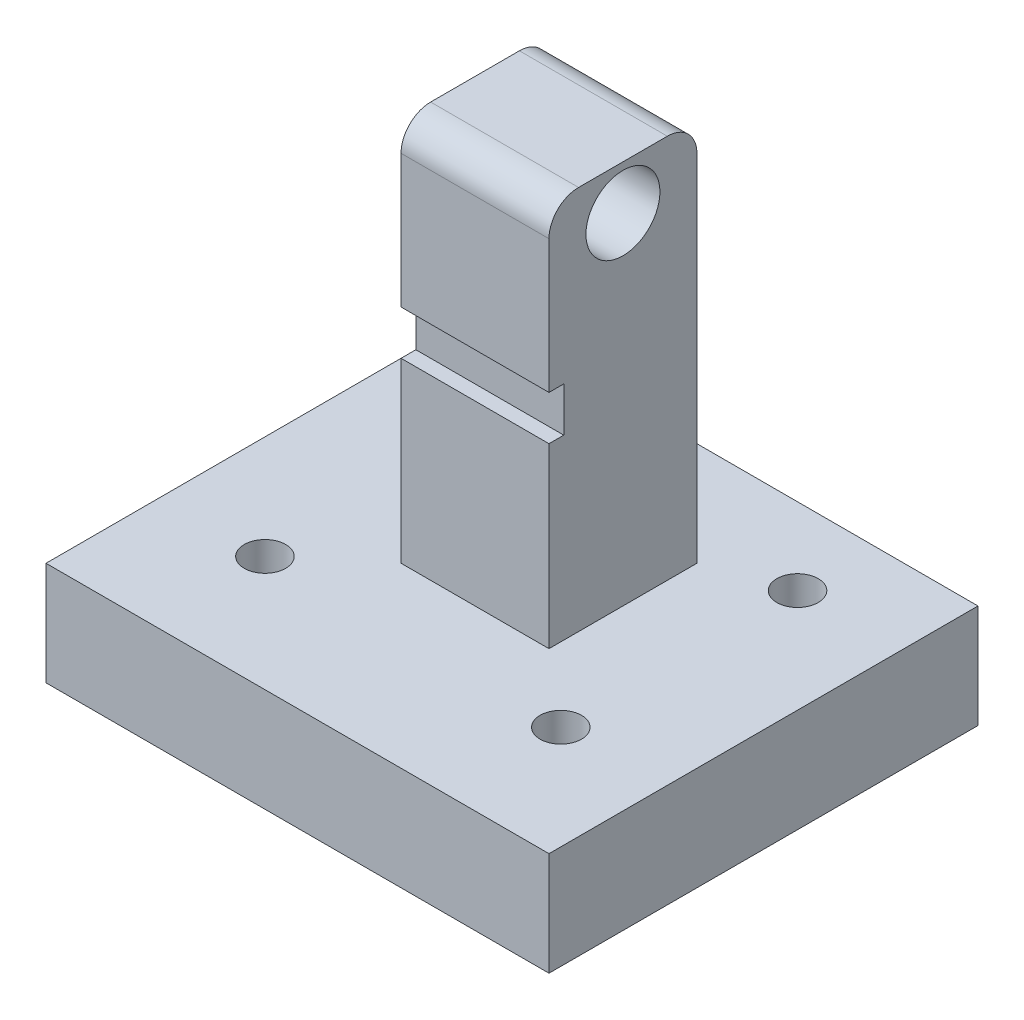
SolidWorks part; units mm, degrees
ref_plane "Front Plane" through (0, 0, 0) normal (0, 0, 1) x (1, 0, 0)
ref_plane "Top Plane" through (0, 0, 0) normal (0, 1, 0) x (1, 0, 0)
ref_plane "Right Plane" through (0, 0, 0) normal (1, 0, 0) x (0, 0, -1)
sketch "Sketch2" plane through (0, 0, 0) normal (0, 0, 1) x (1, 0, 0)
  line L1 (-73.75, 88.375) -> (73.75, 88.375)
  line L2 (-73.75, 88.375) -> (-73.75, -88.375)
  line L3 (-73.75, -88.375) -> (73.75, -88.375)
  line L4 (73.75, 88.375) -> (73.75, -88.375)
  line L5 (-73.75, 88.375) -> (73.75, -88.375) construction
  line L6 (-73.75, -88.375) -> (73.75, 88.375) construction
  point P0 (0, 0)
  dimension "D1" = 147.5
  dimension "D2" = 176.75
extrude "Boss-Extrude1" add sketch "Sketch2" along normal blind 10
sketch "Sketch3" plane through (-73.75, 0, 0) normal (-1, 0, 0) x (0, 0, 1)
  line L0 (0, 88.375) -> (0, -88.375) construction
  line L1 (-7, 88.375) -> (22, 88.375)
  line L2 (-7, 88.375) -> (-7, 73.375)
  line L3 (-7, 73.375) -> (22, 73.375)
  line L4 (22, 88.375) -> (22, 73.375)
  line L5 (10, 88.375) -> (10, -88.375) construction
  line L6 (0, 0) -> (56.8374, 0) construction
  line L7 (22, -88.375) -> (22, -73.375)
  line L8 (-7, -88.375) -> (-7, -73.375)
  line L9 (-7, -88.375) -> (22, -88.375)
  line L10 (-7, -73.375) -> (22, -73.375)
  line L11 (10, 88.375) -> (0, 88.375) construction
  dimension "D1" = 7
  dimension "D2" = 12
  dimension "D3" = 15
  dimension "D4" = 0
extrude "Boss-Extrude2" add sketch "Sketch3" against normal blind 34
ref_plane "Plane1" through (0, 0, 0) normal (1, 0, 0) x (0, 0, -1)
mirror "Mirror1" about plane through (0, 0, 0) normal (1, 0, 0) of "Boss-Extrude2"
sketch "Sketch5" plane through (-73.75, 0, 0) normal (-1, 0, 0) x (0, 0, 1)
  line L0 (10, 73.375) -> (10, -73.375) construction
  line L1 (-35, 0) -> (-35, 43.6802) construction
  line L2 (0, 0) -> (0, 73.375) construction
  line L3 (0, 0) -> (10, 0)
  line L4 (-35, 0) -> (0, 0) construction
  line L5 (-7, 88.375) -> (22, 88.375)
  line L6 (-7, 88.375) -> (-7, 73.375)
  line L7 (-7, 73.375) -> (22, 73.375)
  line L8 (22, 88.375) -> (22, 73.375)
  line L9 (0, 73.375) -> (10, 73.375)
  line L10 (0, 73.375) -> (0, 0)
  line L11 (0, 0) -> (10, 0)
  line L12 (10, 73.375) -> (10, 0)
  line L13 (5, 0) -> (5, -4.9122)
  line L18 (58.2224, 51.916) -> (50.0308, 46.1802)
  line L19 (-7, 73.375) -> (22, 73.375)
  line L20 (-7, 73.375) -> (-7, 63.375)
  line L21 (-7, 63.375) -> (22, 63.375)
  line L22 (22, 73.375) -> (22, 63.375)
  line L23 (50.0308, 46.1802) -> (66.6646, 22.4248)
  line L24 (58.2224, 51.916) -> (74.8561, 28.1606)
  line L25 (74.8561, 28.1606) -> (66.6646, 22.4248)
  line L26 (67.9732, 37.9904) -> (7.8679, -4.0958)
  line L27 (62.2374, 46.1819) -> (2.1321, 4.0958)
  line L28 (2.1321, 4.0958) -> (7.8679, -4.0958)
  line L29 (2.1321, -4.0958) -> (7.8679, 4.0958)
  line L30 (62.2374, -46.1819) -> (2.1321, -4.0958)
  line L31 (67.9732, -37.9904) -> (7.8679, 4.0958)
  line L32 (5, 0) -> (5, 4.9122)
  line L33 (74.8561, -28.1606) -> (66.6646, -22.4248)
  line L34 (58.2224, -51.916) -> (74.8561, -28.1606)
  line L35 (50.0308, -46.1802) -> (66.6646, -22.4248)
  line L36 (58.2224, -51.916) -> (50.0308, -46.1802)
  line L37 (50.0308, 46.1802) -> (66.6646, 22.4248)
  line L38 (-7, 63.375) -> (22, 63.375)
  line L39 (-7, 63.375) -> (-7, 48.375)
  line L40 (-7, 48.375) -> (22, 48.375)
  line L41 (22, 63.375) -> (22, 48.375)
  line L42 (50.0308, 46.1802) -> (37.7436, 37.5766)
  line L43 (37.7436, 37.5766) -> (54.3773, 13.8212)
  line L44 (66.6646, 22.4248) -> (54.3773, 13.8212)
  line L45 (50.0308, -46.1802) -> (66.6646, -22.4248)
  line L46 (66.6646, -22.4248) -> (54.3773, -13.8212)
  line L47 (50.0308, -46.1802) -> (37.7436, -37.5766)
  line L48 (37.7436, -37.5766) -> (54.3773, -13.8212)
  circle A0 centre (-35, 0) radius 110
  point P17 (-35, 0)
  point P31 (5, 0)
  point P34 (5, 0)
  point P51 (5, 0)
  line M9 (10, -73.375) -> (10, 73.375)
  dimension "D3" = 10
  dimension "D1" = 220
  dimension "D2" = 35
  dimension "D5" = 15
  dimension "D4" = 2
  dimension "D6" = 2
extrude "Boss-Extrude3" add sketch "Sketch5" against normal blind 34 contours L31 L26 L23 L27 L12 | L30 L35 L31 L26 M9 | L26 L31 M9 | L44 L23 L26 L43 | L27 L43 L26 L23 | L42 L43 L27 L23 | L48 L47 L35 L30 | L48 L30 L35 L31 | L48 L31 L35 L46
sketch "Sketch8" plane through (0, 0, 22) normal (0, 0, 1) x (1, 0, 0)
  line L1 (73.75, 88.375) -> (-39.75, 88.375)
  line L2 (73.75, 88.375) -> (73.75, -88.375)
  line L3 (73.75, -88.375) -> (-39.75, -88.375)
  line L4 (-39.75, 88.375) -> (-39.75, -88.375)
extrude "Cut-Extrude1" cut sketch "Sketch8" against normal blind 30
sketch "Sketch9" plane through (0, 0, 0) normal (0, 0, -1) x (-1, 0, 0)
  line L0 (39.75, 73.375) -> (39.75, -73.375) construction
  line L4 (39.75, 73.375) -> (73.75, 73.375) construction
  line L6 (0, 0) -> (126.3955, 0) construction
  line L8 (39.75, -73.375) -> (73.75, -73.375) construction
  circle A0 centre (49.75, 58.375) radius 2.5
  circle A2 centre (63.75, 58.375) radius 2.5
  circle A5 centre (49.75, -53.375) radius 2.5
  circle A6 centre (63.75, -53.375) radius 2.5
  dimension "D1" = 5
  dimension "D2" = 14
  dimension "D3" = 10
  dimension "D4" = 15
  dimension "D6" = 5
  dimension "D7" = 20
  dimension "D8" = 10
  dimension "D5" = 2
  dimension "D9" = 2
extrude "Cut-Extrude2" cut sketch "Sketch9" against normal through all
sketch "Sketch10" plane through (0, 0, -7) normal (0, 0, -1) x (-1, 0, 0)
  line L1 (73.75, 88.375) -> (70.75, 88.375)
  line L2 (73.75, 88.375) -> (73.75, 85.375)
  line L3 (73.75, 85.375) -> (70.75, 85.375)
  line L4 (70.75, 88.375) -> (70.75, 85.375)
  dimension "D1" = 3
  dimension "D2" = 3
extrude "Cut-Extrude3" cut sketch "Sketch10" against normal blind 3
sketch "Sketch11" plane through (0, 0, 0) normal (0, 0, -1) x (-1, 0, 0)
  line L0 (39.75, 73.375) -> (39.75, -73.375) construction
  line L1 (39.75, -61.375) -> (73.75, -61.375)
  line L2 (39.75, -61.375) -> (39.75, -73.375)
  line L3 (39.75, -73.375) -> (73.75, -73.375)
  line L4 (73.75, -61.375) -> (73.75, -73.375)
  line L5 (39.75, -65.375) -> (73.75, -65.375)
  line L7 (39.75, -61.375) -> (42.75, -61.375)
  line L8 (39.75, -61.375) -> (39.75, -73.375)
  line L9 (39.75, -73.375) -> (42.75, -73.375)
  line L10 (42.75, -61.375) -> (42.75, -73.375)
  line L11 (73.75, -61.375) -> (70.75, -61.375)
  line L12 (73.75, -61.375) -> (73.75, -73.375)
  line L13 (73.75, -73.375) -> (70.75, -73.375)
  line L14 (70.75, -61.375) -> (70.75, -73.375)
  line L15 (51.75, -65.375) -> (61.75, -65.375)
  line L16 (51.75, -65.375) -> (51.75, -73.375)
  line L17 (51.75, -73.375) -> (61.75, -73.375)
  line L18 (61.75, -65.375) -> (61.75, -73.375)
  line L19 (73.75, -73.375) -> (39.75, -73.375)
  line L20 (73.75, -73.375) -> (73.75, -58.375)
  line L21 (73.75, -58.375) -> (39.75, -58.375)
  line L22 (39.75, -73.375) -> (39.75, -58.375)
  line L23 (61.75, -65.375) -> (51.75, -65.375)
  line L24 (61.75, -65.375) -> (61.75, -58.375)
  line L25 (61.75, -58.375) -> (51.75, -58.375)
  line L26 (51.75, -65.375) -> (51.75, -58.375)
  line L27 (39.75, 88.375) -> (73.75, 88.375)
  line L28 (39.75, 88.375) -> (39.75, -58.375)
  line L29 (39.75, -58.375) -> (73.75, -58.375)
  line L30 (73.75, 88.375) -> (73.75, -58.375)
  circle M11 centre (49.75, -53.375) radius 2.5
  circle M12 centre (63.75, 58.375) radius 2.5
  circle M13 centre (63.75, -53.375) radius 2.5
  circle M14 centre (49.75, 58.375) radius 2.5
  line M15 (73.75, 73.375) -> (39.75, 73.375)
  line M16 (39.75, 73.375) -> (39.75, -73.375)
  line M17 (39.75, -73.375) -> (73.75, -73.375)
  line M18 (73.75, -73.375) -> (73.75, 73.375)
  dimension "D1" = 12
  dimension "D2" = 4
  dimension "D3" = 3
  dimension "D4" = 3
  dimension "D5" = 10
  dimension "D6" = 9
  dimension "D7" = 15
extrude "Cut-Extrude4" cut sketch "Sketch11" against normal through all both and the other way through all contours L16 L5 L10 L3 | L5 L26 L1 L10 | L10 L5 L2 M17 | L10 L1 L5 M16 | L5 L18 L3 L14 | L24 L5 L14 L1 | L1 L14 L5 L4 | L5 L14 M17 M18 | L21 M18 M15 M16 M12 M14 M13 M11 | L24 L1 L21 M18 | L1 L26 L21 M16 | L30 L27 L28 M15
sketch "Sketch13" plane through (-61.75, 0, 0) normal (-1, 0, 0) x (0, 0, 1)
  line L0 (10, -58.375) -> (10, -73.375) construction
  line L1 (10, -73.375) -> (0, -73.375) construction
  circle A0 centre (5, -63.375) radius 2.5
  dimension "D1" = 5
  dimension "D2" = 5
  dimension "D3" = 10
extrude "Cut-Extrude5" cut sketch "Sketch13" against normal through all both and the other way through all
sketch "Sketch14" plane through (-61.75, 0, 0) normal (-1, 0, 0) x (0, 0, 1)
  line L0 (10, -58.375) -> (10, -73.375) construction
  line L1 (0, -58.375) -> (10, -58.375)
  line L2 (0, -58.375) -> (0, -60.375)
  line L3 (0, -60.375) -> (10, -60.375)
  line L4 (10, -58.375) -> (10, -60.375)
  dimension "D1" = 2
extrude "Cut-Extrude6" cut sketch "Sketch14" against normal through all both and the other way through all
fillet "Fillet1" radius 2 2 edges at (-56.75, -60.375, 10) (-56.75, -60.375, 0)
sketch "Sketch15" plane through (0, -88.375, 0) normal (0, -1, 0) x (1, 0, 0)
  line L0 (-39.75, -7) -> (-73.75, -7) construction
  line L1 (-39.75, -7) -> (-39.75, 22) construction
  circle A0 centre (-46.75, -1.8) radius 1.4
  circle A1 centre (-66.75, -1.8) radius 1.4
  circle A2 centre (-66.75, 14.2) radius 1.4
  circle A3 centre (-46.75, 14.2) radius 1.4
  dimension "D1" = 5.2
  dimension "D2" = 7
  dimension "D3" = 2
  dimension "D4" = 2
extrude "Cut-Extrude7" cut sketch "Sketch15" against normal blind 34
sketch "Sketch18" plane through (0, 0, -7) normal (0, 0, -1) x (-1, 0, 0)
  line L0 (39.75, -73.375) -> (73.75, -73.375) construction
  line L1 (39.75, -73.375) -> (51.75, -73.375)
  line L2 (39.75, -73.375) -> (39.75, -81.375)
  line L3 (39.75, -81.375) -> (51.75, -81.375)
  line L4 (51.75, -73.375) -> (51.75, -81.375)
  line L5 (61.75, -73.375) -> (73.75, -73.375)
  line L6 (61.75, -73.375) -> (61.75, -81.375)
  line L7 (61.75, -81.375) -> (73.75, -81.375)
  line L8 (73.75, -73.375) -> (73.75, -81.375)
  line L9 (73.75, -73.375) -> (73.75, -88.375) construction
  dimension "D1" = 12
  dimension "D2" = 12
  dimension "D3" = 8
  dimension "D4" = 8
extrude "Cut-Extrude8" cut sketch "Sketch18" against normal blind 34
sketch "Sketch19" plane through (-61.75, 0, 0) normal (-1, 0, 0) x (0, 0, 1)
  line L0 (22, -81.375) -> (-7, -81.375) construction
  line L1 (-7, -73.375) -> (0, -73.375)
  line L2 (-7, -73.375) -> (-7, -81.375)
  line L3 (-7, -81.375) -> (0, -81.375)
  line L4 (0, -73.375) -> (0, -81.375)
  line L6 (10, -73.375) -> (22, -73.375)
  line L7 (10, -73.375) -> (10, -81.375)
  line L8 (10, -81.375) -> (22, -81.375)
  line L9 (22, -73.375) -> (22, -81.375)
extrude "Cut-Extrude9" cut sketch "Sketch19" against normal blind 34
sketch "Sketch20" plane through (0, -88.375, 0) normal (0, -1, 0) x (1, 0, 0)
  line L1 (-73.75, 22) -> (-39.75, 22)
  line L2 (-73.75, 22) -> (-73.75, -7)
  line L3 (-73.75, -7) -> (-39.75, -7)
  line L4 (-39.75, 22) -> (-39.75, -7)
  circle A0 centre (-66.75, 14.2) radius 1.4
  circle A1 centre (-46.75, 14.2) radius 1.4
  circle A2 centre (-46.75, -1.8) radius 1.4
  circle A3 centre (-66.75, -1.8) radius 1.4
  dimension "D1" = 2
  dimension "D2" = 2
extrude "Boss-Extrude4" add sketch "Sketch20" along normal blind 5
sketch "Sketch21" plane through (0, -81.375, 0) normal (0, 1, 0) x (1, 0, 0)
  line L1 (-73.75, 7) -> (-39.75, 7)
  line L2 (-73.75, 7) -> (-73.75, -22)
  line L3 (-73.75, -22) -> (-39.75, -22)
  line L4 (-39.75, 7) -> (-39.75, -22)
  line L5 (-61.75, 0) -> (-51.75, 0)
  line L6 (-61.75, 0) -> (-61.75, -10)
  line L7 (-61.75, -10) -> (-51.75, -10)
  line L8 (-51.75, 0) -> (-51.75, -10)
extrude "Cut-Extrude10" cut sketch "Sketch21" against normal blind 5
sketch "Sketch22" plane through (0, 0, 10) normal (0, 0, 1) x (1, 0, 0)
  line L0 (-61.75, -62.375) -> (-61.75, -86.375) construction
  line L1 (-61.75, -71.375) -> (-51.75, -71.375)
  line L2 (-61.75, -71.375) -> (-61.75, -74.375)
  line L3 (-61.75, -74.375) -> (-51.75, -74.375)
  line L4 (-51.75, -71.375) -> (-51.75, -74.375)
  line L5 (-51.75, -86.375) -> (-51.75, -62.375) construction
  line L6 (-61.75, -60.375) -> (-51.75, -60.375) construction
  dimension "D1" = 11
  dimension "D2" = 14
extrude "Cut-Extrude11" cut sketch "Sketch22" against normal blind 1
